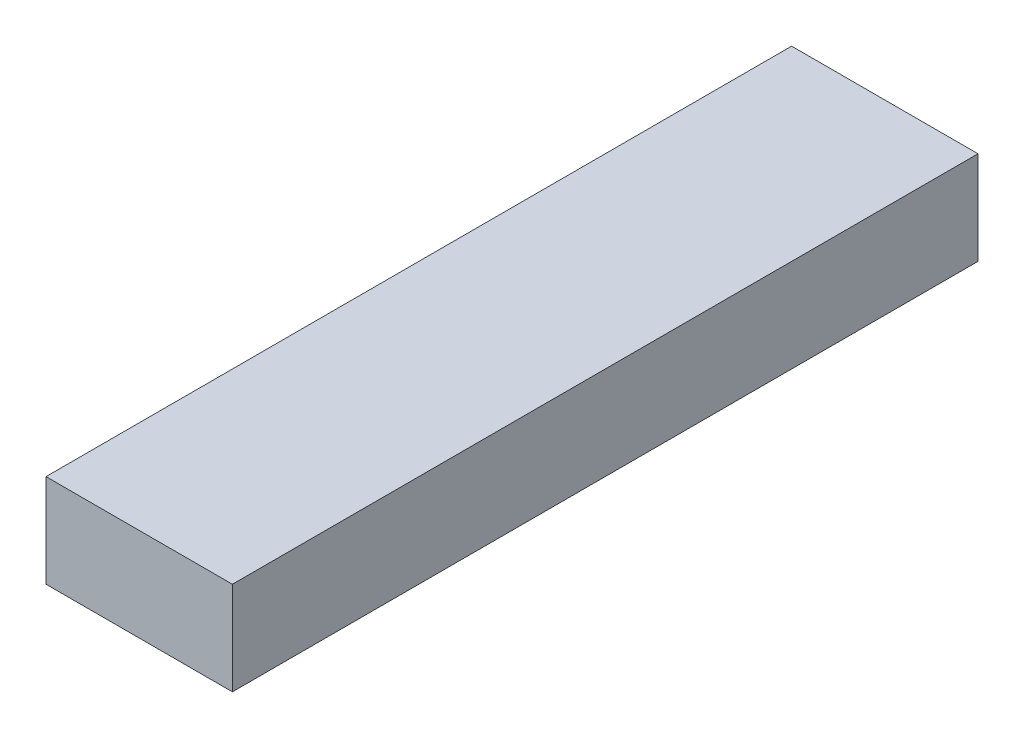
SolidWorks part; units mm, degrees
ref_plane "前视基准面" through (0, 0, 0) normal (0, 0, 1) x (1, 0, 0)
ref_plane "上视基准面" through (0, 0, 0) normal (0, 1, 0) x (1, 0, 0)
ref_plane "右视基准面" through (0, 0, 0) normal (1, 0, 0) x (0, 0, -1)
other "Configuration Table"
sketch "Profile1" plane through (0, 0, 0) normal (0, 0, 1) x (1, 0, 0)
  line L1 (-5, -2.5) -> (5, -2.5)
  line L2 (-5, -2.5) -> (-5, 2.5)
  line L3 (-5, 2.5) -> (5, 2.5)
  line L4 (5, -2.5) -> (5, 2.5)
sketch "Path1" plane through (0, 0, 0) normal (1, 0, 0) x (0, 0, -1)
  line L0 (0, 0) -> (-40, 0)
sweep "modern_sweep_twist1_90" add profiles "Profile1" path "Path1"
